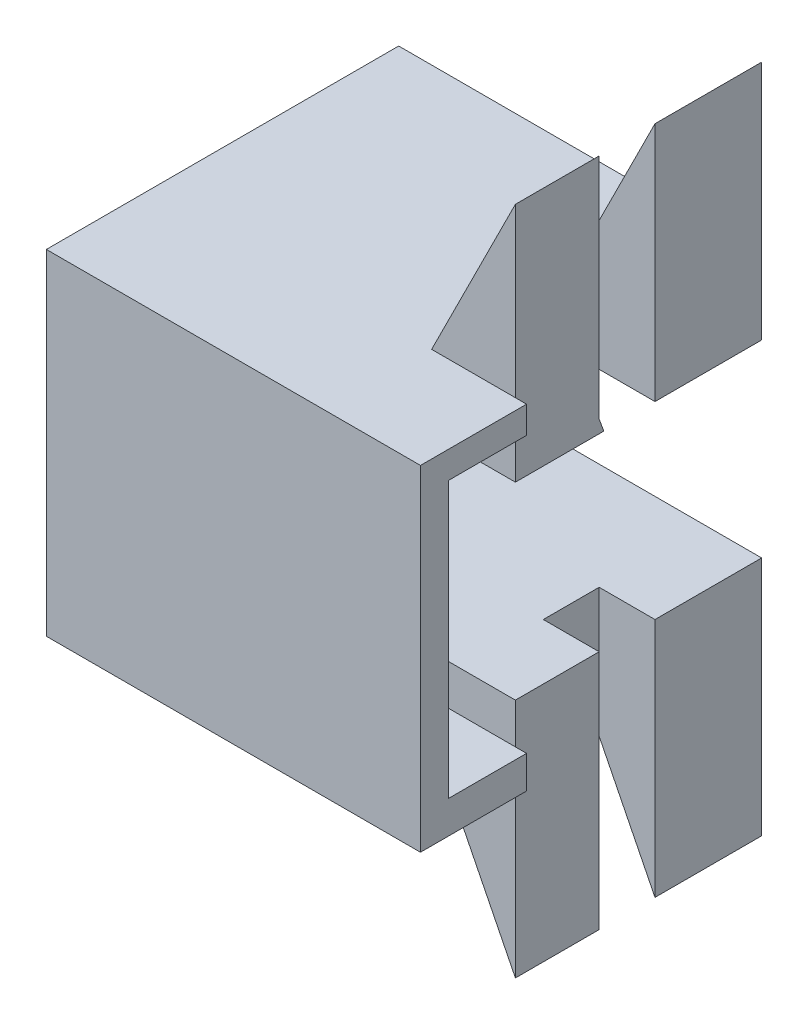
SolidWorks part; units mm, degrees
ref_plane "Front" through (0, 0, 0) normal (0, 0, 1) x (1, 0, 0)
ref_plane "Top" through (0, 0, 0) normal (0, 1, 0) x (1, 0, 0)
ref_plane "Right" through (0, 0, 0) normal (1, 0, 0) x (0, 0, -1)
sketch "草图1" plane through (0, 0, 0) normal (0, 0, 1) x (1, 0, 0)
  line L0 (50, -30) -> (65, -30)
  line L1 (0, 0) -> (50, 0)
  line L2 (0, 0) -> (0, -60)
  line L3 (0, -60) -> (50, -60)
  line L4 (50, 0) -> (50, -60)
  line L5 (65, -90) -> (65, 30)
  line L6 (65, 30) -> (50, 0)
  line L7 (65, -90) -> (50, -60)
  point P9 (65, -30)
  dimension "D1" = 50
  dimension "D2" = 60
  dimension "D3" = 15
  dimension "D4" = 120
extrude "凸台-拉伸1" add sketch "草图1" along normal blind 44.1 contours L4 L1 L2 L3 | L5 L6 L4 L0 | L7 L5 L0 L4
sketch "草图2" plane through (0, 0, 44.1) normal (0, 0, 1) x (1, 0, 0)
  line L0 (65, -90) -> (65, 30) construction
  line L2 (121.5, -46.9) -> (8.5, -46.9)
  line L3 (121.5, -46.9) -> (121.5, -13.1)
  line L4 (121.5, -13.1) -> (8.5, -13.1)
  line L5 (8.5, -46.9) -> (8.5, -13.1)
  line L6 (121.5, -46.9) -> (8.5, -13.1) construction
  line L7 (121.5, -13.1) -> (8.5, -46.9) construction
  point P0 (65, -30)
  point P1 (65, -30)
  dimension "D1" = 33.8
  dimension "D2" = 56.5
extrude "切除-拉伸1" cut sketch "草图2" against normal through all
sketch "草图3" plane through (65, 0, 0) normal (1, 0, 0) x (0, 0, -1)
  line L0 (-44.1, 30) -> (0, -90)
  line L1 (-44.1, 30) -> (0, 30) construction
  line L2 (-29.1, -90) -> (-19.1, -90)
  line L3 (-29.1, -90) -> (-29.1, 30)
  line L4 (-29.1, 30) -> (-19.1, 30)
  line L5 (-19.1, -90) -> (-19.1, 30)
  line L6 (-29.1, -90) -> (-19.1, 30) construction
  line L7 (-29.1, 30) -> (-19.1, -90) construction
  line L8 (-44.1, -13.1) -> (-44.1, 30) construction
  point P4 (-22.05, -30)
  point P5 (-22.05, -30)
  point P15 (-24.1, -30)
  line M3 (-44.1, -13.1) -> (0, -13.1)
  line M9 (0, 30) -> (-44.1, 30)
  dimension "D1" = 10
  dimension "D2" = 20
extrude "切除-拉伸2" cut sketch "草图3" against normal blind 10 contours L2 L5 L0 L3 M3 | L5 L3 L0 M3 M9
sketch "草图4" plane through (0, 0, 44.1) normal (0, 0, 1) x (1, 0, 0)
  line L0 (0, 0) -> (0, -60)
  line L1 (67, -60) -> (0, -60)
  line L2 (8.5, -13.1) -> (8.5, -46.9) construction
  line L3 (0, 0) -> (67, 0)
  line L5 (67, 0) -> (67, -4.8365)
  line L6 (67, -4.8365) -> (28.5, -4.8365)
  line L7 (28.5, -4.8365) -> (28.5, -54.1585)
  line L8 (28.5, -54.1585) -> (67, -54.1585)
  line L9 (67, -54.1585) -> (67, -60)
  point P7 (0, 0)
  point P9 (71.5664, 0)
  dimension "D1" = 58.5
  dimension "D2" = 58.5
  dimension "D3" = 20
extrude "凸台-拉伸2" add sketch "草图4" along normal blind 14
sketch "草图5" plane through (0, 0, 58.1) normal (0, 0, 1) x (1, 0, 0)
  line L0 (67, -60) -> (67, -54.1585) construction
  line L1 (67, -60) -> (0, -60)
  line L2 (67, -60) -> (67, 0)
  line L3 (67, 0) -> (0, 0)
  line L4 (0, -60) -> (0, 0)
  line M1 (67, 0) -> (0, 0)
  line M2 (0, 0) -> (0, -60)
  line M3 (0, -60) -> (67, -60)
  line M4 (67, -60) -> (67, -54.1585)
  line M5 (67, -54.1585) -> (28.5, -54.1585)
  line M6 (28.5, -54.1585) -> (28.5, -4.8365)
  line M7 (28.5, -4.8365) -> (67, -4.8365)
  line M8 (67, -4.8365) -> (67, 0)
extrude "凸台-拉伸3" add sketch "草图5" along normal blind 5 contours L2 L3 M8 M7 M6 M5 | M8 M1 M2 M3 M4 M5 M6 M7
